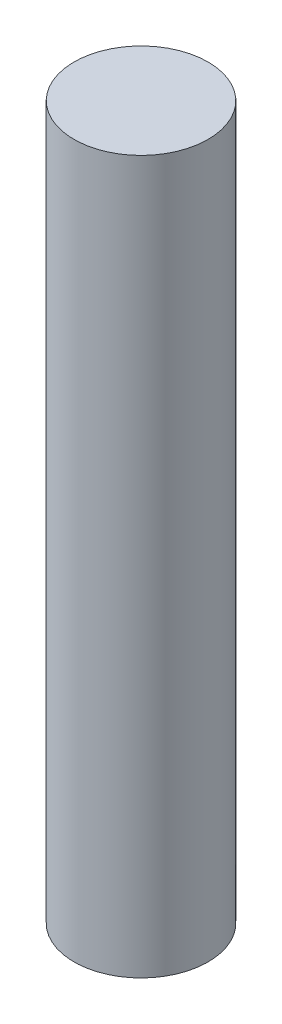
SolidWorks part; units mm, degrees
ref_plane "Front Plane" through (0, 0, 0) normal (0, 0, 1) x (1, 0, 0)
ref_plane "Top Plane" through (0, 0, 0) normal (0, 1, 0) x (1, 0, 0)
ref_plane "Right Plane" through (0, 0, 0) normal (1, 0, 0) x (0, 0, -1)
sketch "Sketch1" plane through (0, 0, 0) normal (0, 0, 1) x (1, 0, 0)
  line L0 (-188.0884, 0) -> (188.0884, 0) construction
  line L1 (0, -226.1446) -> (0, 226.1446) construction
  line L3 (0, 0) -> (112, 0)
  line L4 (0, 0) -> (0, 1190)
  line L5 (0, 1190) -> (112, 1190)
  line L6 (112, 0) -> (112, 1190)
  point P4 (0, 0)
  point P8 (0, 0)
  dimension "D1" = 112
  dimension "D2" = 1190
revolve "Revolve1" add sketch "Sketch1" angle 360 about L1
